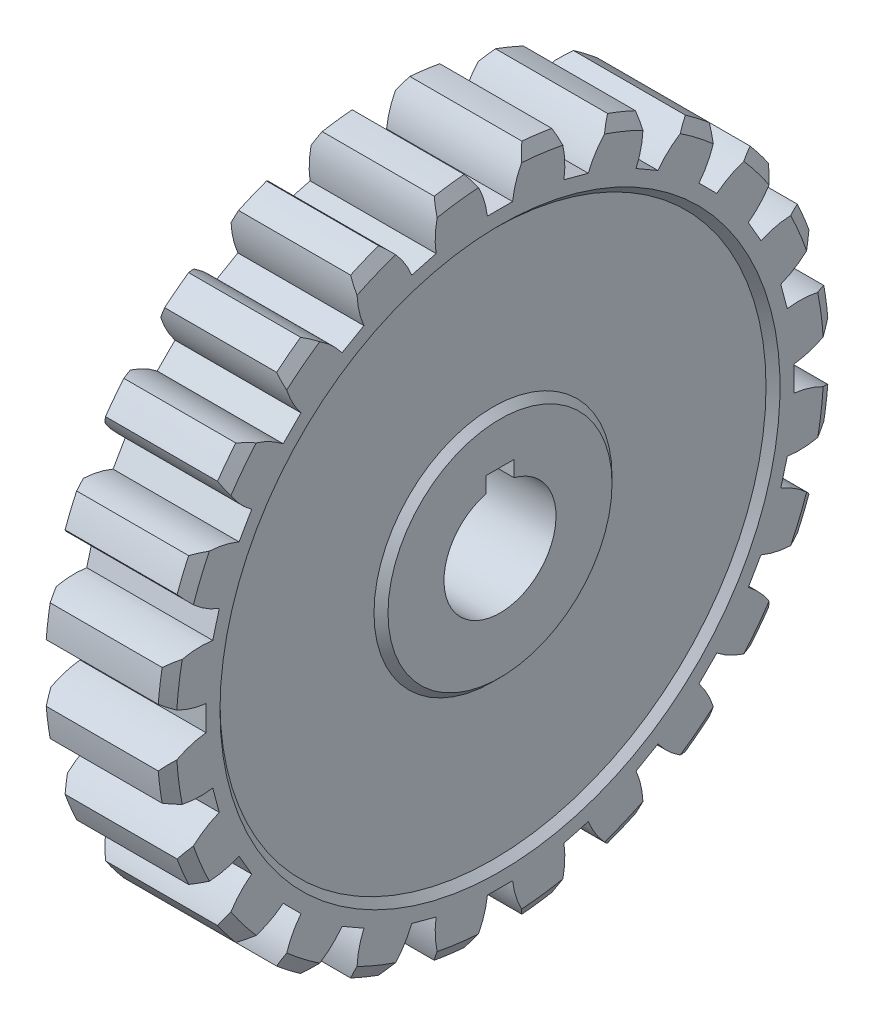
SolidWorks part; units mm, degrees
ref_plane "Front Plane" through (0, 0, 0) normal (0, 0, 1) x (1, 0, 0)
ref_plane "Top Plane" through (0, 0, 0) normal (0, 1, 0) x (1, 0, 0)
ref_plane "Right Plane" through (0, 0, 0) normal (1, 0, 0) x (0, 0, -1)
sketch "Sketch2" plane through (0, 0, 0) normal (0, 0, 1) x (1, 0, 0)
  line L0 (0, 100.2095) -> (0, -107.6105) construction
  line L1 (-113.728, 0) -> (125.6266, 0) construction
  line L2 (-12.7, 76.2) -> (12.7, 76.2)
  line L3 (12.7, 76.2) -> (14.2875, 73.4504)
  line L4 (-12.7, 76.2) -> (-14.2875, 73.4504)
  line L5 (14.2875, 73.4504) -> (14.2875, 63.5)
  line L6 (-14.2875, 73.4504) -> (-14.2875, 63.5)
  line L7 (14.2875, 63.5) -> (12.7, 61.9125)
  line L8 (-14.2875, 63.5) -> (-12.7, 61.9125)
  line L9 (12.7, 61.9125) -> (12.7, 26.9875)
  line L10 (-12.7, 61.9125) -> (-12.7, 26.9875)
  line L11 (12.7, 26.9875) -> (14.2875, 25.4)
  line L12 (-12.7, 26.9875) -> (-14.2875, 25.4)
  line L13 (14.2875, 25.4) -> (14.2875, 12.7)
  line L14 (-14.2875, 25.4) -> (-14.2875, 12.7)
  line L15 (14.2875, 12.7) -> (-14.2875, 12.7)
  point P8 (0, 76.2)
  point P20 (0, 12.7)
  dimension "D1" = 76.2
  dimension "D2" = 63.5
  dimension "D3" = 12.7
  dimension "D4" = 25.4
  dimension "D5" = 25.4
  dimension "D6" = 25.4
  dimension "D7" = 28.575
  dimension "D8" = 28.575
  dimension "D9" = 150
  dimension "D10" = 135
  dimension "D11" = 135
revolve "Revolve1" add sketch "Sketch2" angle 360 about L1
sketch "Sketch3" plane through (-14.2875, 0, 0) normal (-1, 0, 0) x (0, 0, 1)
  line L0 (0, 76.2) -> (0, -76.2) construction
  line L1 (-2.8575, 66.675) -> (2.8575, 66.675)
  circle A0 centre (0, 0) radius 76.2 construction
  arc A1 (2.8575, 66.675) -> (6.5405, 75.9188) centre (21.7818, 64.4906) cw
  arc A2 (-2.8575, 66.675) -> (-6.5405, 75.9188) centre (-21.7818, 64.4906) ccw
  arc A3 (-6.5405, 75.9188) -> (6.5405, 75.9188) centre (0, 0) cw
  point P5 (0, 66.675)
  circle M4 centre (0, 0) radius 73.4504
  dimension "D1" = 19.05
  dimension "D2" = 66.675
  dimension "D3" = 5.715
  dimension "D4" = 6.5405
  dimension "D5" = 13.081
extrude "Cut-Extrude1" cut sketch "Sketch3" against normal through all contours L0 A3 A2 M4 | A3 L0 A1 M4 | L0 L1 A1 M4 | L0 A2 L1 M4
pattern_circular "CirPattern1" count 24 over 360 about axis through (0, 0, 0) along (1, 0, 0) of "Cut-Extrude1"
sketch "Sketch4" plane through (-14.2875, 0, 0) normal (-1, 0, 0) x (0, 0, 1)
  line L0 (0, 66.675) -> (0, -66.675) construction
  line L1 (-2.8575, 66.675) -> (2.8575, 66.675) construction
  line L2 (2.8575, -66.675) -> (-2.8575, -66.675) construction
  line L3 (-3.175, 15.875) -> (3.175, 15.875)
  line L4 (3.175, 15.875) -> (3.175, 12.2967)
  line L5 (-3.175, 15.875) -> (-3.175, 12.2967)
  circle A0 centre (0, 0) radius 12.7 construction
  arc A1 (0, -12.7) -> (-3.175, 12.2967) centre (0, 0) ccw
  point P12 (0, 15.875)
  circle M2 centre (0, 0) radius 12.7
  dimension "D1" = 6.35
  dimension "D2" = 15.875
extrude "Cut-Extrude2" cut sketch "Sketch4" against normal through all contours L0 L3 L5 M2 | L3 L0 A1 L4
sketch "Sketch5" [suppressed] plane through (-14.2875, 0, 0) normal (-1, 0, 0) x (0, 0, 1)
  line L1 (0, 0) -> (-87.2962, 0)
  line L2 (0, 0) -> (0, -89.6911)
  line L3 (0, -89.6911) -> (-87.2962, -89.6911)
  line L4 (-87.2962, 0) -> (-87.2962, -89.6911)
  line L5 (0, 0) -> (86.2926, 0)
  line L6 (0, 0) -> (0, -101.4134)
  line L7 (0, -101.4134) -> (86.2926, -101.4134)
  line L8 (86.2926, 0) -> (86.2926, -101.4134)
  arc M1 (3.175, 12.2967) -> (-3.175, 12.2967) centre (0, 0) cw
  circle M5 centre (0, 0) radius 25.4
extrude "Cut-Extrude3" [suppressed] cut sketch "Sketch5" against normal through all contours L1 L4 L3 L2 M5 | L8 L5 L2 L6 L7 M5 | L2 L1 M1 M5 | L5 L2 M1 M5
